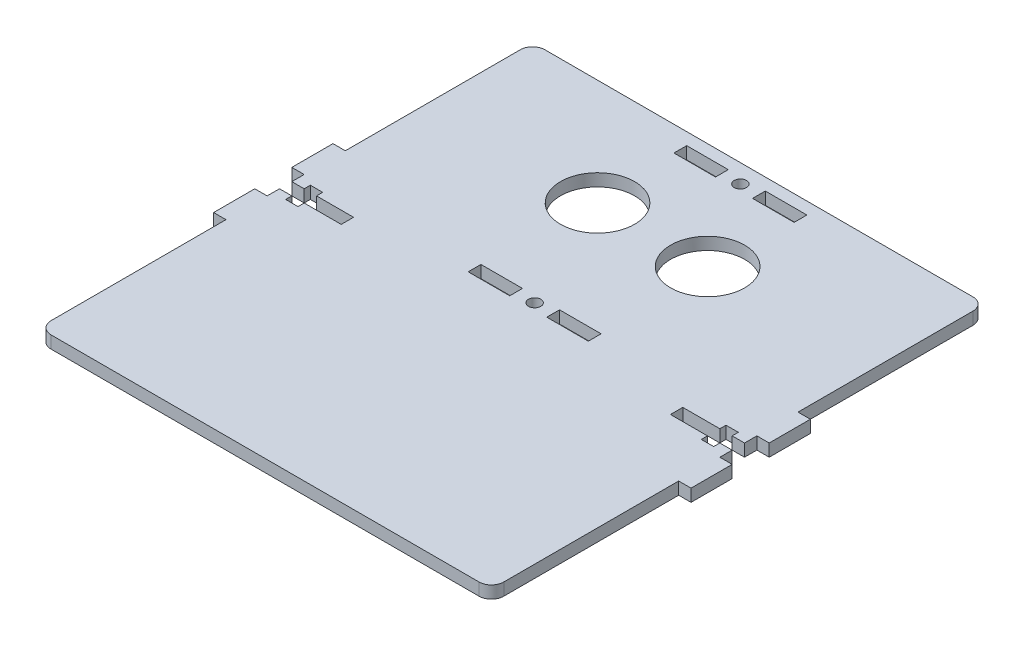
SolidWorks part; units mm, degrees
ref_plane "Front Plane" through (0, 0, 0) normal (0, 0, 1) x (1, 0, 0)
ref_plane "Top Plane" through (0, 0, 0) normal (0, 1, 0) x (1, 0, 0)
ref_plane "Right Plane" through (0, 0, 0) normal (1, 0, 0) x (0, 0, -1)
sketch "Sketch1" plane through (0, 0, 0) normal (0, 1, 0) x (1, 0, 0)
  line L0 (55, 120) -> (55, 0) construction
  line L1 (0, 0) -> (110, 0)
  line L2 (0, 0) -> (0, 120)
  line L3 (0, 120) -> (110, 120)
  line L4 (110, 0) -> (110, 120)
  line L5 (0, 60) -> (110, 60) construction
  line L6 (107, 63) -> (107, 57)
  line L7 (0, 61.5) -> (15, 61.5)
  line L8 (0, 61.5) -> (0, 58.5)
  line L9 (0, 58.5) -> (15, 58.5)
  line L10 (15, 61.5) -> (15, 58.5)
  line L11 (3, 63) -> (6, 63)
  line L12 (3, 63) -> (3, 57)
  line L13 (3, 57) -> (6, 57)
  line L14 (6, 63) -> (6, 57)
  line L15 (107, 57) -> (104, 57)
  line L16 (104, 63) -> (104, 57)
  line L17 (107, 63) -> (104, 63)
  line L18 (110, 61.5) -> (110, 58.5)
  line L19 (110, 58.5) -> (95, 58.5)
  line L20 (95, 61.5) -> (95, 58.5)
  line L21 (110, 61.5) -> (95, 61.5)
  line L22 (0, 55.5) -> (0, 45.5)
  line L23 (0, 64.5) -> (-3, 64.5)
  line L24 (0, 64.5) -> (0, 74.5)
  line L25 (0, 74.5) -> (-3, 74.5)
  line L26 (-3, 64.5) -> (-3, 74.5)
  line L27 (0, 55.5) -> (-3, 55.5)
  line L28 (-3, 55.5) -> (-3, 45.5)
  line L29 (0, 45.5) -> (-3, 45.5)
  line L30 (110, 55.5) -> (110, 45.5)
  line L31 (110, 45.5) -> (113, 45.5)
  line L32 (113, 55.5) -> (113, 45.5)
  line L33 (110, 55.5) -> (113, 55.5)
  line L34 (110, 64.5) -> (110, 74.5)
  line L35 (110, 64.5) -> (113, 64.5)
  line L36 (113, 64.5) -> (113, 74.5)
  line L37 (110, 74.5) -> (113, 74.5)
  line L38 (40.4, 65.5) -> (69.6, 65.5) construction
  line L39 (69.6, 67.05) -> (69.6, 63.95)
  line L40 (40.4, 67.05) -> (50.5, 67.05)
  line L41 (40.4, 67.05) -> (40.4, 63.95)
  line L42 (40.4, 63.95) -> (50.5, 63.95)
  line L43 (50.5, 67.05) -> (50.5, 63.95)
  line L44 (69.6, 67.05) -> (59.5, 67.05)
  line L45 (59.5, 67.05) -> (59.5, 63.95)
  line L46 (69.6, 63.95) -> (59.5, 63.95)
  line L47 (40.4, 115.5) -> (90.3807, 115.5) construction
  line L48 (69.6, 113.95) -> (69.6, 117.05)
  line L49 (40.4, 113.95) -> (50.5, 113.95)
  line L50 (40.4, 113.95) -> (40.4, 117.05)
  line L51 (40.4, 117.05) -> (50.5, 117.05)
  line L52 (50.5, 113.95) -> (50.5, 117.05)
  line L53 (69.6, 117.05) -> (59.5, 117.05)
  line L54 (59.5, 113.95) -> (59.5, 117.05)
  line L55 (69.6, 113.95) -> (59.5, 113.95)
  circle A0 centre (55, 65.5) radius 1.5
  circle A1 centre (55, 115.5) radius 1.5
  point P13 (0, 60)
  point P18 (3, 60)
  point P51 (40.4, 65.5)
  point P64 (40.4, 115.5)
  dimension "D13" = 10.1
  dimension "D12" = 3
  dimension "D16" = 3
  dimension "D1" = 120
  dimension "D2" = 110
  dimension "D3" = 3
  dimension "D4" = 3
  dimension "D5" = 6
  dimension "D6" = 3
  dimension "D7" = 15
  dimension "D8" = 10
  dimension "D9" = 4.5
  dimension "D10" = 3
  dimension "D11" = 65.5
  dimension "D14" = 3.1
  dimension "D15" = 4.5
  dimension "D17" = 10.1
  dimension "D18" = 4.5
  dimension "D19" = 3.1
  dimension "D20" = 4.5
extrude "Boss-Extrude1" add sketch "Sketch1" along normal blind 3 contours L21 L4 L3 L2 L7 L12 L11 L14 L10 L9 L13 L1 L19 L6 L15 L16 L20 L17 | L33 L4 L31 L32 | L37 L4 L35 L36 | L29 L2 L27 L28 | L26 L23 L2 L25
fillet "Fillet1" radius 3 4 edges at (110, 1.5, 0) (0, 1.5, 0) (0, 1.5, -120) (110, 1.5, -120)
sketch "Sketch2" plane through (0, 3, 0) normal (0, 1, 0) x (1, 0, 0)
  line L0 (55, 120) -> (55, 0) construction
  line L1 (3, 120) -> (107, 120) construction
  line L2 (3, 0) -> (107, 0) construction
  line L3 (41.625, 94.16) -> (68.375, 94.16) construction
  circle A0 centre (41.625, 94.16) radius 9
  circle A1 centre (68.375, 94.16) radius 9
  dimension "D1" = 18
  dimension "D2" = 26.75
  dimension "D3" = 25.84
extrude "Cut-Extrude1" cut sketch "Sketch2" against normal blind 10
